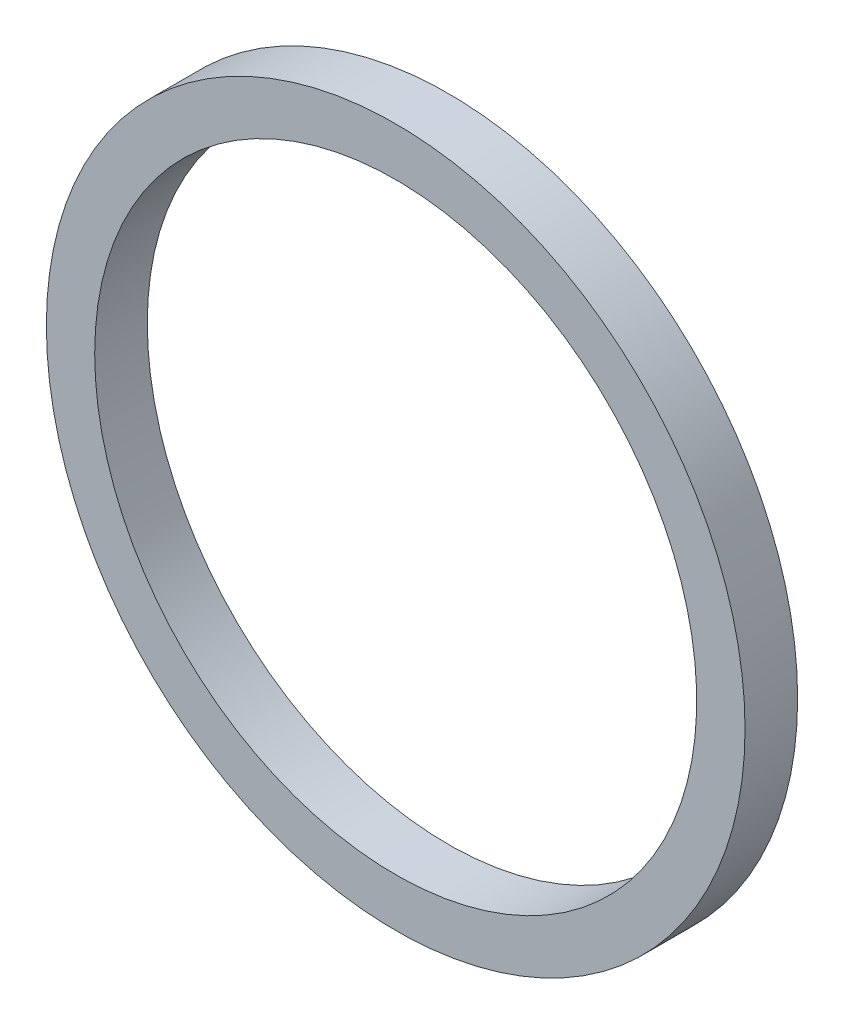
SolidWorks part; units mm, degrees
other "Markup1"
sketch "Sketch2" plane through (22.05, -22.05, 3.32) normal (0.0429, -0.0737, 0.9964) x (0.9979, 0.0514, -0.0392)
ref_plane "Front" through (0, 0, 0) normal (0, 0, 1) x (1, 0, 0)
ref_plane "Top" through (0, 0, 0) normal (0, 1, 0) x (1, 0, 0)
ref_plane "Right" through (0, 0, 0) normal (1, 0, 0) x (0, 0, -1)
sketch "Sketch1" plane through (0, 0, 0) normal (0, 0, 1) x (1, 0, 0)
  circle A0 centre (0, 0) radius 19
  circle A1 centre (0, 0) radius 22.05
  dimension "D1" = 44.1
  dimension "D2" = 38
extrude "Boss-Extrude1" add sketch "Sketch1" along normal blind 3.32
